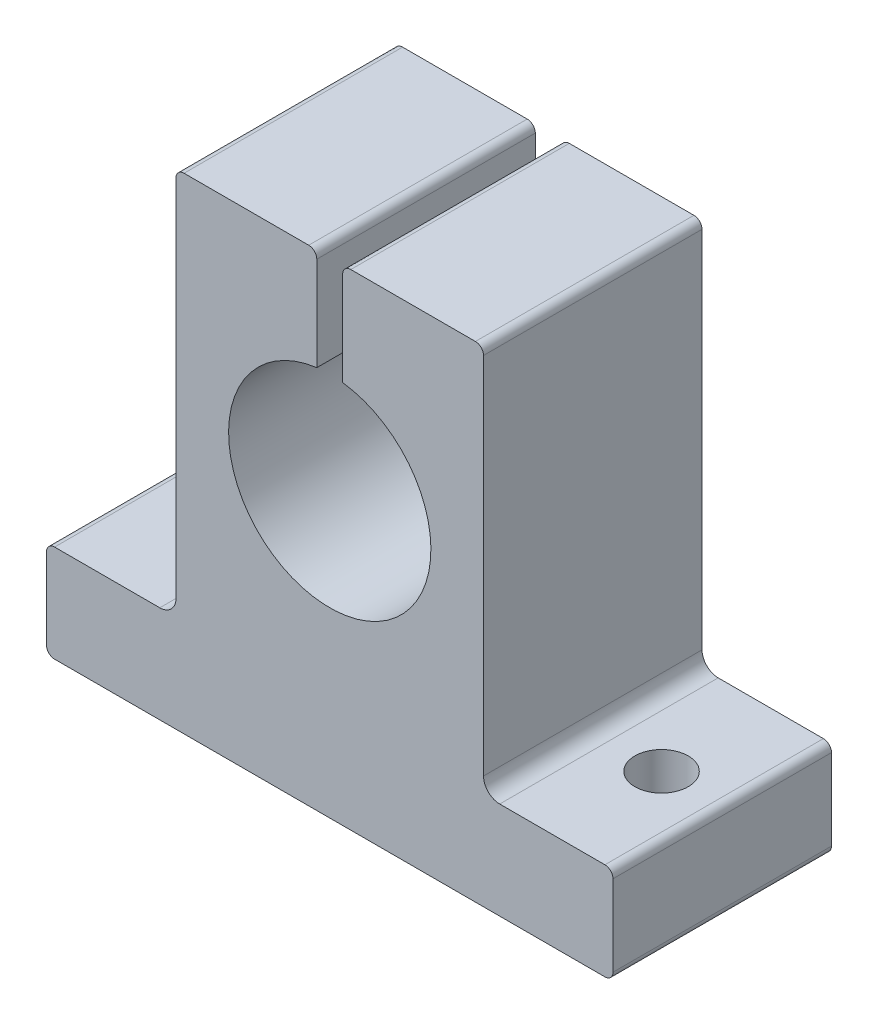
SolidWorks part; units mm, degrees
ref_plane "Front" through (0, 0, 0) normal (0, 0, 1) x (1, 0, 0)
ref_plane "Top" through (0, 0, 0) normal (0, 1, 0) x (1, 0, 0)
ref_plane "Right" through (0, 0, 0) normal (1, 0, 0) x (0, 0, -1)
sketch "Sketch1" plane through (0, 0, 0) normal (0, 0, 1) x (1, 0, 0)
  line L0 (-35, -34) -> (-35, -24)
  line L1 (-34, -23) -> (-21, -23)
  line L2 (-19, -21) -> (-19, 24)
  line L3 (-18, 25) -> (-2.6, 25)
  line L4 (-1.6, 24) -> (-1.6, 12.3972)
  line L5 (-34, -35) -> (34, -35)
  line L6 (0, 0) -> (0, 26.113) construction
  line L7 (0, 0) -> (0, -35) construction
  line L8 (1.6, 24) -> (1.6, 12.3972)
  line L9 (18, 25) -> (2.6, 25)
  line L10 (19, -21) -> (19, 24)
  line L11 (34, -23) -> (21, -23)
  line L12 (35, -34) -> (35, -24)
  arc A0 (-1.6, 12.3972) -> (1.6, 12.3972) centre (0, 0) ccw
  arc A1 (-21, -23) -> (-19, -21) centre (-21, -21) ccw
  arc A2 (-2.6, 25) -> (-1.6, 24) centre (-2.6, 24) cw
  arc A3 (-19, 24) -> (-18, 25) centre (-18, 24) cw
  arc A4 (-35, -24) -> (-34, -23) centre (-34, -24) cw
  arc A5 (-35, -34) -> (-34, -35) centre (-34, -34) ccw
  arc A6 (2.6, 25) -> (1.6, 24) centre (2.6, 24) ccw
  arc A7 (19, 24) -> (18, 25) centre (18, 24) ccw
  arc A8 (21, -23) -> (19, -21) centre (21, -21) cw
  arc A9 (35, -24) -> (34, -23) centre (34, -24) ccw
  arc A10 (35, -34) -> (34, -35) centre (34, -34) cw
  point P19 (-35, -23)
  point P22 (-35, -35)
  dimension "D1" = 60
  dimension "D6" = 1.6
  dimension "D7" = 12.5
  dimension "D8" = 2
  dimension "D9" = 1
  dimension "D2" = 35
  dimension "D3" = 35
  dimension "D4" = 12
  dimension "D5" = 19
extrude "Boss-Extrude1" add sketch "Sketch1" along normal blind 27
sketch "Sketch2" plane through (0, -23, 0) normal (0, 1, 0) x (1, 0, 0)
  line L0 (-27.5, 0) -> (-27.5, -27) construction
  line L1 (-21, 0) -> (-34, 0) construction
  line L2 (-21, -27) -> (-34, -27) construction
  line L3 (-34, -13.5) -> (-21, -13.5) construction
  line L4 (-34, -27) -> (-34, 0) construction
  line L5 (-21, -27) -> (-21, 0) construction
  circle A0 centre (-27.5, -13.5) radius 3.3
  dimension "D1" = 6.6
extrude "Cut-Extrude1" cut sketch "Sketch2" against normal through all
mirror "Mirror1" about plane through (0, 0, 0) normal (1, 0, 0) of "Cut-Extrude1"
